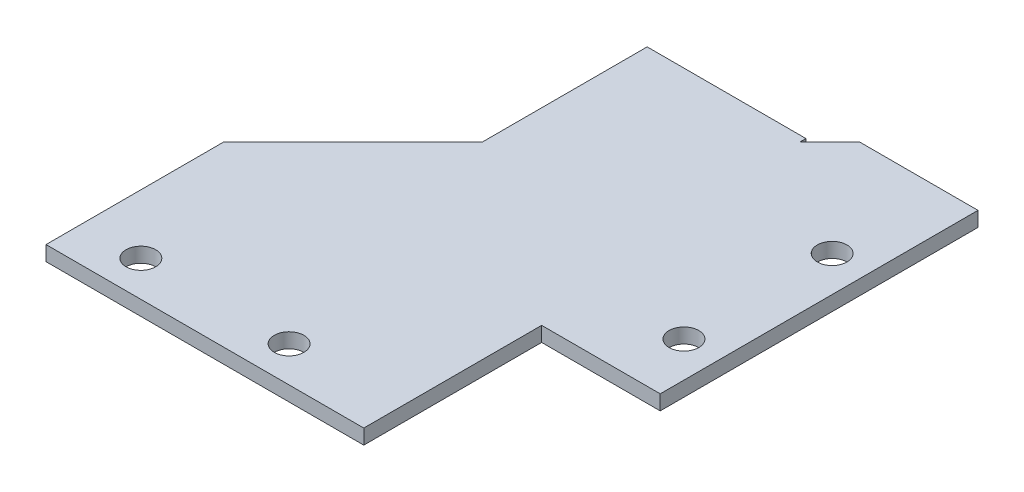
SolidWorks part; units mm, degrees
ref_plane "Front Plane" through (0, 0, 0) normal (0, 0, 1) x (1, 0, 0)
ref_plane "Top Plane" through (0, 0, 0) normal (0, 1, 0) x (1, 0, 0)
ref_plane "Right Plane" through (0, 0, 0) normal (1, 0, 0) x (0, 0, -1)
sketch "Sketch1" plane through (0, 0, 0) normal (0, 1, 0) x (1, 0, 0)
  line L0 (0, 38.1) -> (68.072, 106.172)
  line L1 (0, 0) -> (68.072, 0)
  line L2 (0, 0) -> (0, 38.1)
  line L3 (0, 38.1) -> (68.072, 38.1)
  line L4 (68.072, 0) -> (68.072, 38.1)
  line L5 (68.072, 106.172) -> (68.072, 38.1)
  line L7 (68.072, 38.1) -> (93.472, 38.1)
  line L8 (68.072, 38.1) -> (68.072, 106.172)
  line L9 (68.072, 106.172) -> (93.472, 106.172)
  line L10 (93.472, 38.1) -> (93.472, 106.172)
  line L11 (68.072, 0) -> (93.472, 0)
  line L12 (68.072, 0) -> (68.072, 38.1)
  line L13 (68.072, 38.1) -> (93.472, 38.1)
  line L14 (68.072, 0) -> (68.072, 38.1)
  line L15 (68.072, 38.1) -> (93.472, 38.1)
  line L16 (93.472, 0) -> (93.472, 38.1)
  dimension "D1" = 68.072
  dimension "D2" = 38.1
  dimension "D3" = 68.072
  dimension "D4" = 25.4
extrude "Boss-Extrude1" add sketch "Sketch1" along normal blind 3.175 contours L1 L4 L3 L2 | L5 L0 L3 | L7 L10 L9 L5
sketch "Sketch2" plane through (0, 3.175, 0) normal (0, 1, 0) x (1, 0, 0)
  line L0 (0, 0) -> (68.072, 0) construction
  line L1 (0, 0) -> (0, 38.1) construction
  line L6 (93.472, 38.1) -> (93.472, 106.172) construction
  line L7 (68.072, 38.1) -> (93.472, 38.1) construction
  circle A0 centre (12.7, 7.62) radius 3.175
  circle A1 centre (44.45, 7.62) radius 3.175
  circle A2 centre (85.852, 50.8) radius 3.175
  circle A5 centre (85.852, 82.55) radius 3.175
  circle A6 centre (88.392, 50.8) radius 3.175 [skipped]
  circle A7 centre (88.392, 82.55) radius 3.175 [skipped]
  dimension "D1" = 6.35
  dimension "D2" = 7.62
  dimension "D3" = 12.7
  dimension "D5" = 6.35
  dimension "D6" = 7.62
  dimension "D7" = 12.7
  dimension "D4" = 2
  dimension "D8" = 2
  dimension "D9" = 2
extrude "Cut-Extrude1" cut sketch "Sketch2" against normal through all
sketch "Sketch3" plane through (0, 3.175, 0) normal (0, 1, 0) x (1, 0, 0)
  line L0 (93.472, 38.1) -> (93.472, 106.172) construction
  line L1 (27.7114, 46.5226) -> (61.722, 46.5226)
  line L2 (27.7114, 46.5226) -> (27.7114, 101.0646)
  line L3 (27.7114, 101.0646) -> (61.722, 101.0646)
  line L4 (61.722, 46.5226) -> (61.722, 101.0646)
  dimension "D1" = 34.0106
  dimension "D2" = 31.75
extrude "Boss-Extrude2" add sketch "Sketch3" against normal blind 3.175
